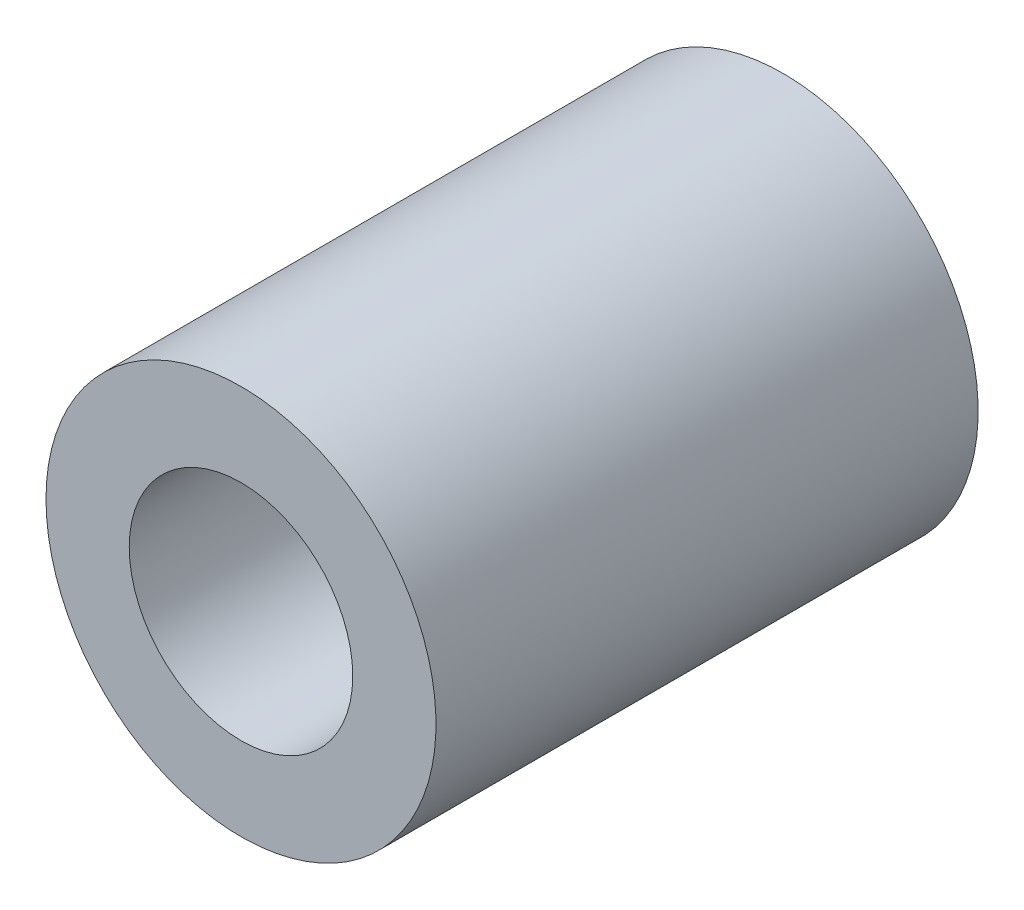
SolidWorks part; units mm, degrees
material "Copper"
ref_plane "Front Plane" through (0, 0, 0) normal (0, 0, 1) x (1, 0, 0)
ref_plane "Top Plane" through (0, 0, 0) normal (0, 1, 0) x (1, 0, 0)
ref_plane "Right Plane" through (0, 0, 0) normal (1, 0, 0) x (0, 0, -1)
sketch "Sketch4" plane through (0, 0, 0) normal (0, 0, 1) x (1, 0, 0)
  circle A0 centre (0, 0) radius 23.5
  circle A1 centre (0, 0) radius 41
  dimension "D1" = 47
  dimension "D2" = 82
extrude "Boss-Extrude2" add sketch "Sketch4" along normal blind 114
